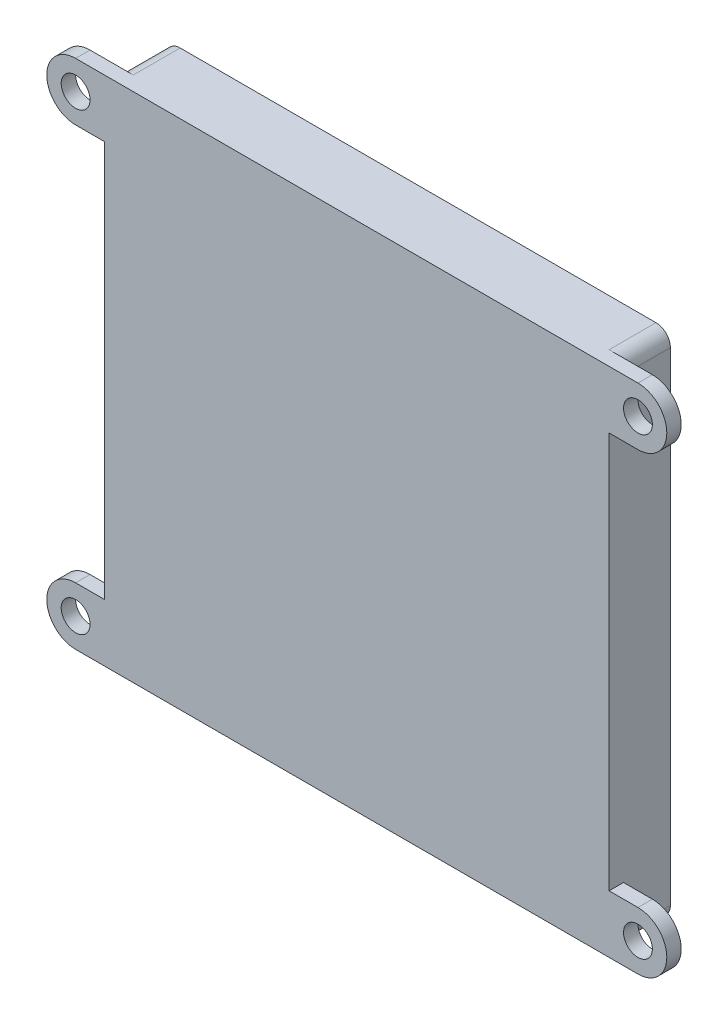
SolidWorks part; units mm, degrees
ref_plane "Front Plane" through (0, 0, 0) normal (0, 0, 1) x (1, 0, 0)
ref_plane "Top Plane" through (0, 0, 0) normal (0, 1, 0) x (1, 0, 0)
ref_plane "Right Plane" through (0, 0, 0) normal (1, 0, 0) x (0, 0, -1)
sketch "Sketch1" plane through (0, 0, 0) normal (0, 0, 1) x (1, 0, 0)
  line L0 (0, 0) -> (0, 31.5) construction
  line L1 (-39, 31.5) -> (39, 31.5) construction
  line L2 (-39, 35.5) -> (39, 35.5)
  line L3 (-39, 27.5) -> (39, 27.5)
  line L4 (55, 0) -> (-55, 0) construction
  line L5 (-39, -31.5) -> (39, -31.5) construction
  line L6 (-39, -35.5) -> (39, -35.5)
  line L7 (-39, -27.5) -> (39, -27.5)
  line L9 (-35, 27.5) -> (35, 27.5)
  line L10 (-35, 27.5) -> (-35, -27.5)
  line L11 (-35, -27.5) -> (35, -27.5)
  line L12 (35, 27.5) -> (35, -27.5)
  line L13 (-35, 27.5) -> (35, -27.5) construction
  line L14 (-35, -27.5) -> (35, 27.5) construction
  arc A0 (-39, 35.5) -> (-39, 27.5) centre (-39, 31.5) ccw
  arc A1 (39, 27.5) -> (39, 35.5) centre (39, 31.5) ccw
  circle A2 centre (39, 31.5) radius 2
  circle A3 centre (-39, 31.5) radius 2
  circle A4 centre (-39, -31.5) radius 2
  circle A5 centre (39, -31.5) radius 2
  arc A6 (-39, -35.5) -> (-39, -27.5) centre (-39, -31.5) cw
  arc A7 (39, -27.5) -> (39, -35.5) centre (39, -31.5) cw
  point P5 (0, 31.5)
  point P20 (0, -31.5)
  dimension "D3" = 4
  dimension "D4" = 4
  dimension "D5" = 4
  dimension "D1" = 31.5
  dimension "D2" = 78
  dimension "D6" = 55
  dimension "D7" = 70
extrude "Boss-Extrude1" add sketch "Sketch1" along normal blind 2 contours L12 L3 L10 L7 | L3 A1 L2 A0 A3 A2 | A7 L7 A6 L6 A4 A5
sketch "Sketch2" plane through (0, 0, 0) normal (0, 0, 1) x (1, 0, 0)
  line L0 (-39, -35.5) -> (39, -35.5) construction
  line L1 (-35, 35.5) -> (35, 35.5)
  line L2 (-35, 35.5) -> (-35, -35.5)
  line L3 (-35, -35.5) -> (35, -35.5)
  line L4 (35, 35.5) -> (35, -35.5)
  line L5 (-35, 35.5) -> (35, -35.5) construction
  line L6 (-35, -35.5) -> (35, 35.5) construction
  point P0 (0, 0)
extrude "Boss-Extrude2" add sketch "Sketch2" against normal blind 6.5
fillet "Fillet1" radius 2 4 edges at (35, -35.5, -3.25) (-35, -35.5, -3.25) (-35, 35.5, -3.25) (35, 35.5, -3.25)
